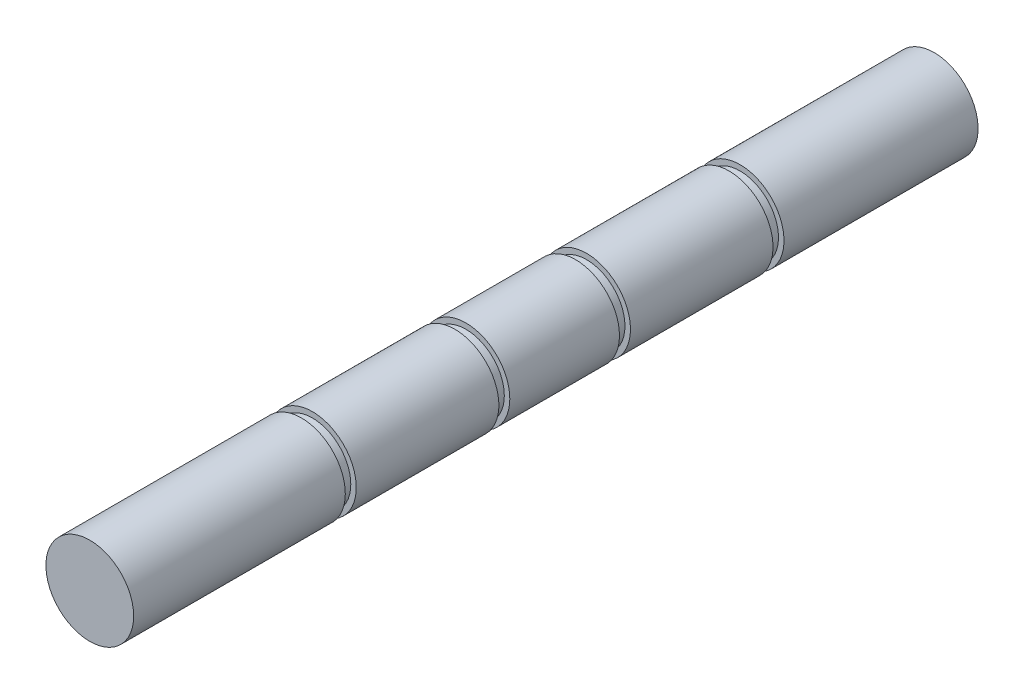
SolidWorks part; units mm, degrees
ref_plane "Front Plane" through (0, 0, 0) normal (0, 0, 1) x (1, 0, 0)
ref_plane "Top Plane" through (0, 0, 0) normal (0, 1, 0) x (1, 0, 0)
ref_plane "Right Plane" through (0, 0, 0) normal (1, 0, 0) x (0, 0, -1)
sketch "Sketch1" plane through (0, 0, 0) normal (0, 0, 1) x (1, 0, 0)
  circle A0 centre (0, 0) radius 3.5
  dimension "D1" = 7
extrude "Boss-Extrude1" add sketch "Sketch1" along normal blind 77
sketch "Sketch3" plane through (0, 0, 0) normal (0, 0, -1) x (-1, 0, 0)
  circle A0 centre (0, 0) radius 3.5
  circle A1 centre (0, 0) radius 4
  dimension "D1" = 8
  dimension "D2" = 7
extrude "Boss-Extrude2" add sketch "Sketch3" against normal blind 17.7
ref_plane "Plane1" through (0, 0, 18.7) normal (0, 0, 1) x (1, 0, 0)
sketch "Sketch6" plane through (0, 0, 18.7) normal (0, 0, 1) x (1, 0, 0)
  circle A0 centre (0, 0) radius 3
  circle A1 centre (0, 0) radius 4
extrude "Boss-Extrude3" add sketch "Sketch6" along normal blind 13
ref_plane "Plane2" through (0, 0, 32.7) normal (0, 0, 1) x (1, 0, 0)
sketch "Sketch7" plane through (0, 0, 32.7) normal (0, 0, 1) x (1, 0, 0)
  circle A0 centre (0, 0) radius 3
  circle A1 centre (0, 0) radius 4
extrude "Boss-Extrude4" add sketch "Sketch7" along normal blind 10
ref_plane "Plane3" through (0, 0, 43.7) normal (0, 0, 1) x (1, 0, 0)
sketch "Sketch8" plane through (0, 0, 43.7) normal (0, 0, 1) x (1, 0, 0)
  circle A0 centre (0, 0) radius 3
  circle A1 centre (0, 0) radius 4
extrude "Boss-Extrude5" add sketch "Sketch8" along normal blind 13
ref_plane "Plane4" through (0, 0, 57.7) normal (0, 0, 1) x (1, 0, 0)
sketch "Sketch9" plane through (0, 0, 57.7) normal (0, 0, 1) x (1, 0, 0)
  circle A0 centre (0, 0) radius 3
  circle A1 centre (0, 0) radius 4
extrude "Boss-Extrude6" add sketch "Sketch9" along normal up to surface (19.3 mm away) up to face at (3.5, 0, 77)
